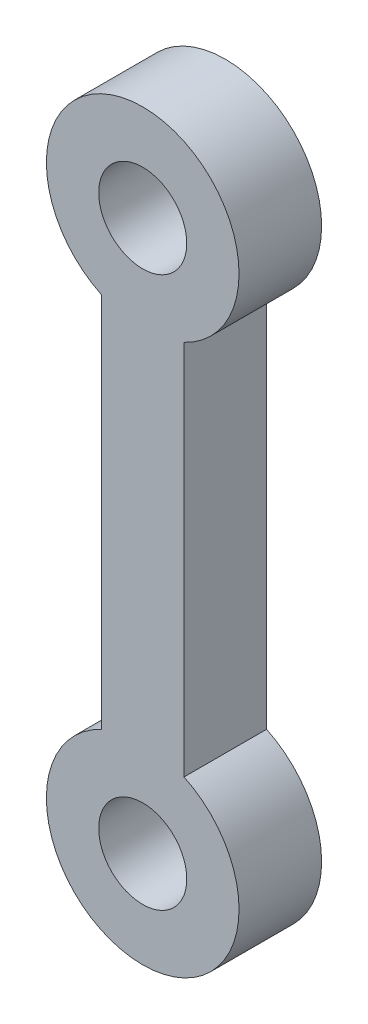
SolidWorks part; units mm, degrees
ref_plane "Front Plane" through (0, 0, 0) normal (0, 0, 1) x (1, 0, 0)
ref_plane "Top Plane" through (0, 0, 0) normal (0, 1, 0) x (1, 0, 0)
ref_plane "Right Plane" through (0, 0, 0) normal (1, 0, 0) x (0, 0, -1)
sketch "Sketch1" plane through (0, 0, 0) normal (0, 0, 1) x (1, 0, 0)
  line L0 (-1.5, 0) -> (1.5, 0)
  line L5 (-1.5, 0) -> (-1.5, -20)
  line L6 (1.5, 0) -> (1.5, -20)
  line L7 (-1.5, -20) -> (1.5, -20)
  circle A0 centre (0, 0) radius 3.5
  circle A1 centre (0, -20) radius 3.5
  dimension "D1" = 7
  dimension "D2" = 7
  dimension "D3" = 20
  dimension "D4" = 1.5
  dimension "D5" = 1.5
extrude "Boss-Extrude1" add sketch "Sketch1" along normal blind 3 contours L6 A0 L5 L0 | L5 A0 L6 L0 | A1 L6 A0 L5 | L6 A1 L5 L7 | L5 A1 L6 L7
sketch "Sketch2" plane through (0, 0, 3) normal (0, 0, 1) x (1, 0, 0)
  circle A0 centre (0, 0) radius 1.6
  circle A1 centre (0, -20) radius 1.6
  dimension "D1" = 3.2
  dimension "D2" = 3.2
extrude "Cut-Extrude1" cut sketch "Sketch2" against normal blind 3 contours A1 | A0
